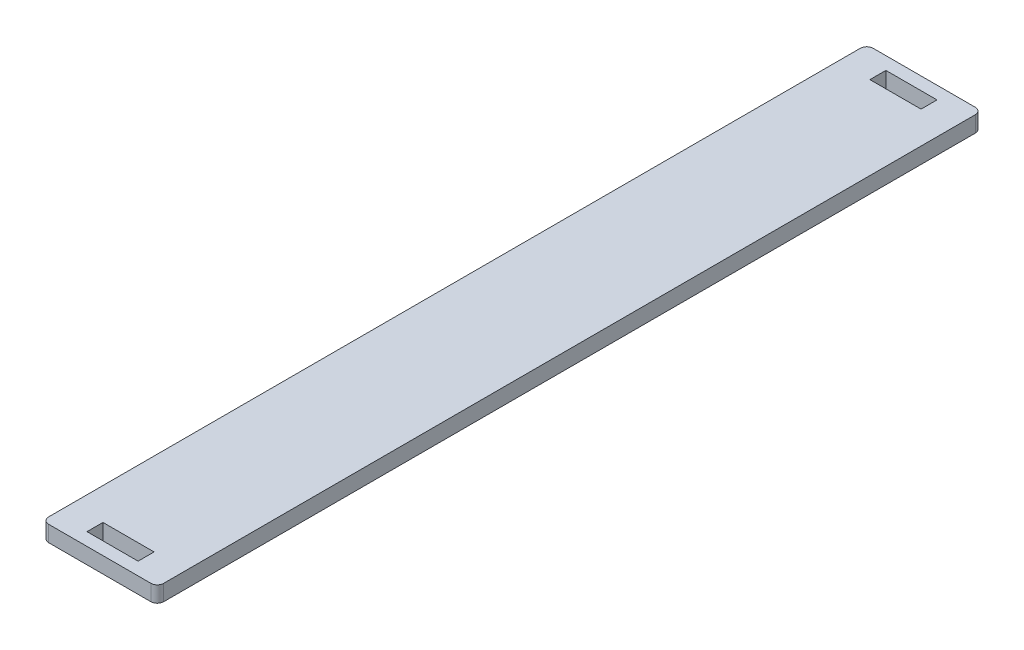
SolidWorks part; units mm, degrees
material "Beech"
ref_plane "Front" through (0, 0, 0) normal (0, 0, 1) x (1, 0, 0)
ref_plane "Top" through (0, 0, 0) normal (0, 1, 0) x (1, 0, 0)
ref_plane "Right" through (0, 0, 0) normal (1, 0, 0) x (0, 0, -1)
sketch "Sketch1" plane through (0, 0, 0) normal (0, 1, 0) x (1, 0, 0)
  line L0 (10.2041, 0) -> (-10.2041, 0) construction
  line L1 (-9, -64.5) -> (9, -64.5)
  line L2 (-9, -64.5) -> (-9, 64.5)
  line L3 (-9, 64.5) -> (9, 64.5)
  line L4 (9, -64.5) -> (9, 64.5)
  line L5 (-9, -64.5) -> (9, 64.5) construction
  line L6 (-9, 64.5) -> (9, -64.5) construction
  line L7 (-4, 60) -> (4, 60)
  line L8 (-4, 60) -> (-4, 62.5)
  line L9 (-4, 62.5) -> (4, 62.5)
  line L10 (4, 60) -> (4, 62.5)
  line L11 (-4, 60) -> (4, 62.5) construction
  line L12 (-4, 62.5) -> (4, 60) construction
  line L13 (-4, -62.5) -> (4, -62.5)
  line L14 (4, -60) -> (4, -62.5)
  line L15 (-4, -60) -> (4, -60)
  line L16 (-4, -60) -> (-4, -62.5)
  point P0 (0, 0)
  point P6 (0, 61.25)
  dimension "D1" = 129
  dimension "D2" = 2
  dimension "D3" = 2.5
  dimension "D4" = 8
  dimension "D5" = 18
extrude "Boss-Extrude1" add sketch "Sketch1" along normal blind 2.5
fillet "Fillet1" radius 1 4 edges at (-9, 1.25, -64.5) (9, 1.25, -64.5) (9, 1.25, 64.5) (-9, 1.25, 64.5)
